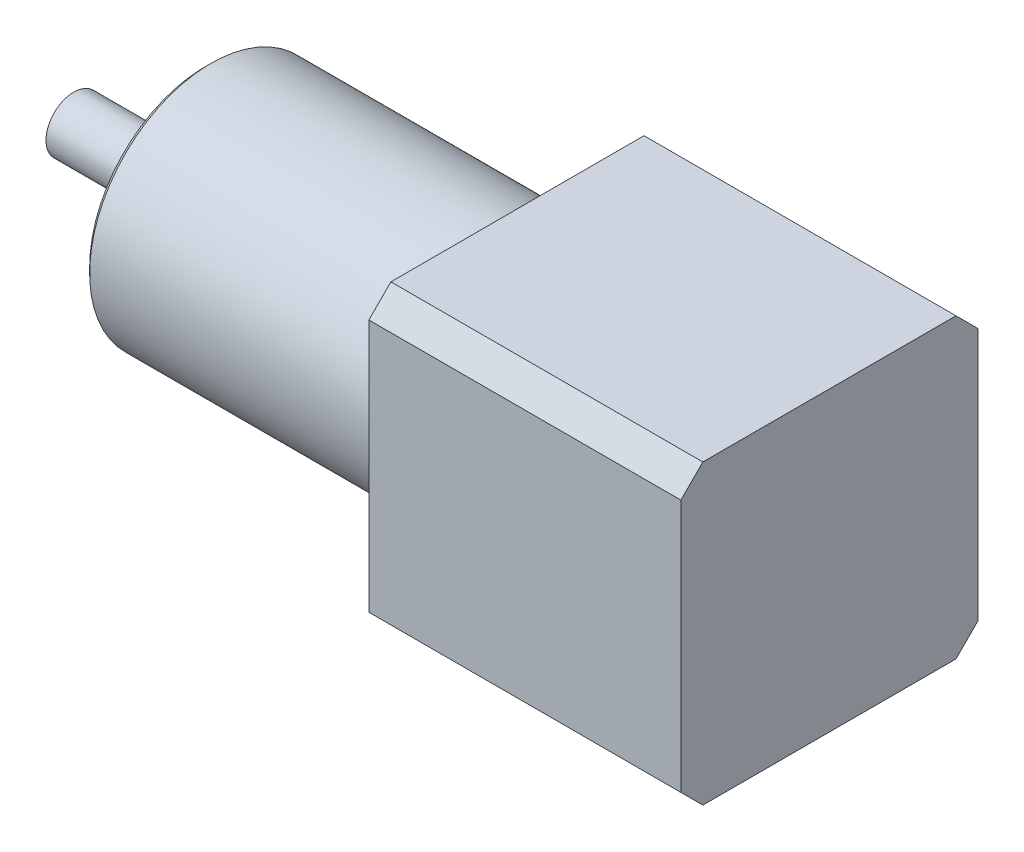
SolidWorks part; units mm, degrees
ref_plane "Front" through (0, 0, 0) normal (0, 0, 1) x (1, 0, 0)
ref_plane "Top" through (0, 0, 0) normal (0, 1, 0) x (1, 0, 0)
ref_plane "Right" through (0, 0, 0) normal (1, 0, 0) x (0, 0, -1)
sketch "Sketch1" plane through (0, 0, 0) normal (1, 0, 0) x (0, 0, -1)
  line L1 (-21.4313, -21.4312) -> (21.4312, -21.4312)
  line L2 (-21.4313, -21.4312) -> (-21.4313, 21.4312)
  line L3 (-21.4313, 21.4312) -> (21.4312, 21.4312)
  line L4 (21.4312, -21.4312) -> (21.4312, 21.4312)
  line L5 (-21.4313, -21.4312) -> (21.4312, 21.4312) construction
  line L6 (-21.4313, 21.4312) -> (21.4312, -21.4312) construction
  point P0 (0, 0)
  dimension "D1" = 42.8625
extrude "Boss-Extrude1" add sketch "Sketch1" against normal blind 45
sketch "Sketch4" plane through (-45, 0, 0) normal (-1, 0, 0) x (0, 0, 1)
  circle A0 centre (0, 0) radius 17.5
  dimension "D1" = 35
extrude "Boss-Extrude2" add sketch "Sketch4" along normal blind 45
sketch "Sketch5" plane through (-90, 0, 0) normal (-1, 0, 0) x (0, 0, 1)
  circle A0 centre (0, 0) radius 4
  dimension "D1" = 8
extrude "Boss-Extrude3" add sketch "Sketch5" along normal blind 19
chamfer "Chamfer1" distance 3.175 angle 45 4 edges at (-22.5, -21.4312, 21.4313) (-22.5, 21.4312, 21.4313) (-22.5, 21.4312, -21.4312) (-22.5, -21.4312, -21.4312)
chamfer "Chamfer2" distance 0.7937 angle 45 1 edges at (-90, 0, 17.5)
